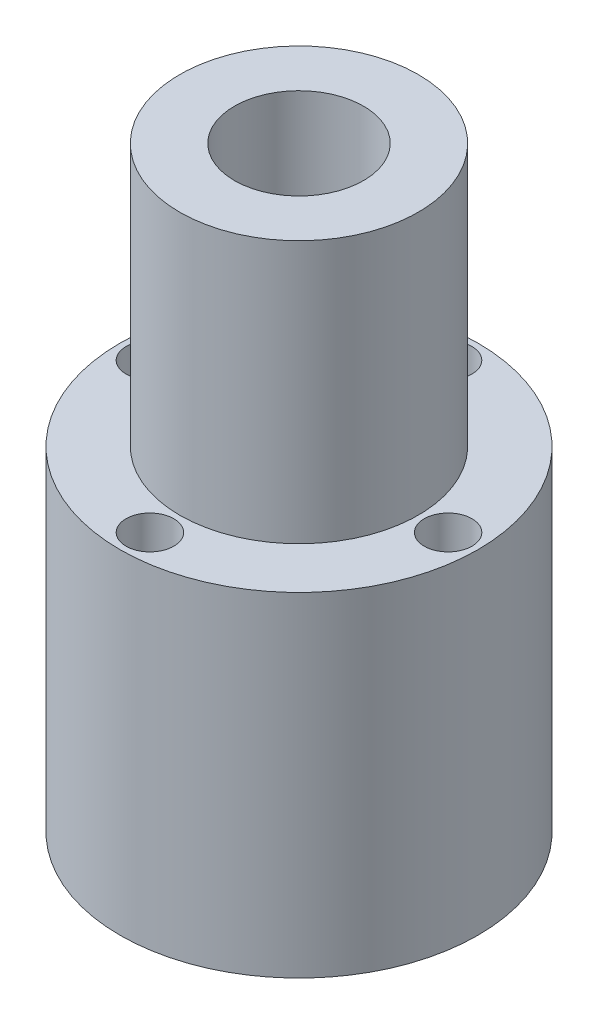
SolidWorks part; units mm, degrees
material "Brass"
ref_plane "Front Plane" through (0, 0, 0) normal (0, 0, 1) x (1, 0, 0)
ref_plane "Top Plane" through (0, 0, 0) normal (0, 1, 0) x (1, 0, 0)
ref_plane "Right Plane" through (0, 0, 0) normal (1, 0, 0) x (0, 0, -1)
sketch "Sketch1" plane through (0, 0, 0) normal (0, 1, 0) x (1, 0, 0)
  circle A0 centre (0, 0) radius 2.7051
  circle A1 centre (0, 0) radius 5
  dimension "D1" = 10
  dimension "D2" = 5.4102
extrude "Boss-Extrude1" add sketch "Sketch1" along normal blind 11
sketch "Sketch2" plane through (0, 0, 0) normal (0, 1, 0) x (1, 0, 0)
  circle A0 centre (0, 0) radius 1.75
  circle A1 centre (0, 0) radius 7.5
  circle A2 centre (0, 0) radius 6.25 construction
  circle A3 centre (0, 6.25) radius 1
  circle A4 centre (6.25, 0) radius 1
  circle A5 centre (0, -6.25) radius 1
  circle A6 centre (-6.25, 0) radius 1
  circle A7 centre (0, 0) radius 5 construction
  dimension "D1" = 3.5
  dimension "D2" = 15
  dimension "D3" = 2
  dimension "D4" = 10
  dimension "D5" = 12.5
extrude "Boss-Extrude2" add sketch "Sketch2" against normal blind 14
sketch "Sketch3" plane through (0, 0, 0) normal (0, 1, 0) x (1, 0, 0)
  circle A0 centre (0, 0) radius 2.1
  dimension "D1" = 4.2
extrude "Cut-Extrude1" cut sketch "Sketch3" along normal blind 6 from surface at -14 starting at face at (-6.25, -14, 1)
